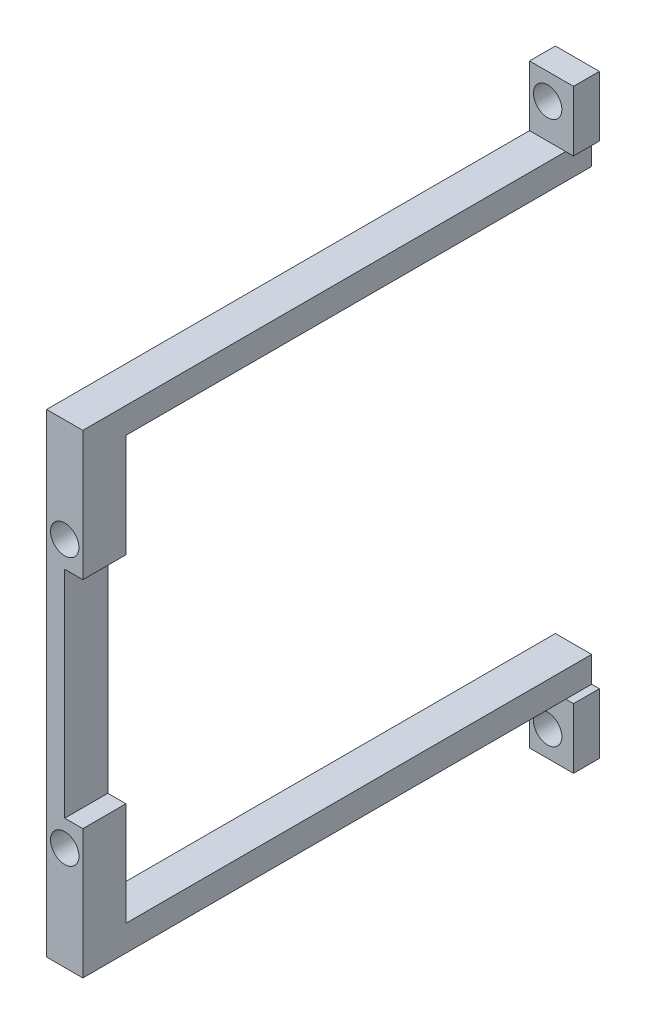
SolidWorks part; units mm, degrees
ref_plane "前视基准面" through (0, 0, 0) normal (0, 0, 1) x (1, 0, 0)
ref_plane "上视基准面" through (0, 0, 0) normal (0, 1, 0) x (1, 0, 0)
ref_plane "右视基准面" through (0, 0, 0) normal (1, 0, 0) x (0, 0, -1)
sketch "草图1" plane through (0, 0, 0) normal (0, 0, 1) x (1, 0, 0)
  line L0 (0, 0) -> (0, -49)
  line L1 (0, -49) -> (4.2, -49)
  line L2 (4.2, -49) -> (4.2, 0)
  line L3 (4.2, 0) -> (0, 0)
extrude "凸台-拉伸1" add sketch "草图1" along normal blind 5
sketch "草图5" plane through (0, 0, 5) normal (0, 0, 1) x (1, 0, 0)
  line L0 (0, -24.5) -> (4.2, -24.5) construction
  line L1 (0, 0) -> (0, -49) construction
  line L2 (4.2, -49) -> (4.2, 0) construction
  line L3 (2.1, -24.5) -> (2.1, -9) construction
  circle A0 centre (2.1, -9) radius 1.65
  circle A1 centre (2.1, -40) radius 1.65
  dimension "D2" = 3.3
  dimension "D1" = 15.5
extrude "切除-拉伸2" cut sketch "草图5" against normal blind 5
sketch "草图6" plane through (0, 0, 5) normal (0, 0, 1) x (1, 0, 0)
  line L0 (0, -49) -> (0, -52)
  line L1 (0, -52) -> (4.2, -52)
  line L2 (4.2, -52) -> (4.2, -49)
  line L3 (4.2, -49) -> (0, -49)
  line L4 (0, -24.5) -> (4.2, -24.5) construction
  line L5 (0, 0) -> (0, -49) construction
  line L6 (4.2, -49) -> (4.2, 0) construction
  line L7 (4.2, 3) -> (4.2, 0)
  line L8 (0, 3) -> (4.2, 3)
  line L9 (0, 0) -> (0, 3)
  line L10 (4.2, 0) -> (0, 0)
  dimension "D1" = 3
  dimension "D2" = 3
extrude "凸台-拉伸2" add sketch "草图6" against normal blind 59
sketch "草图11" plane through (0, 0, -54) normal (0, 0, -1) x (-1, 0, 0)
  line L0 (-2.1, 3) -> (-5.1, 3)
  line L1 (-4.2, 3) -> (0, 3) construction
  line L2 (-2.1, 3) -> (0, 3)
  line L3 (0, 3) -> (0, 10)
  line L4 (0, 10) -> (-5.1, 10)
  line L5 (-5.1, 10) -> (-5.1, 3)
  line L6 (-4.2, -24.5) -> (0, -24.5) construction
  line L7 (-4.2, -49) -> (-4.2, 0) construction
  line L8 (0, 0) -> (0, -49) construction
  line L9 (-2.1, 0) -> (-2.1, 7) construction
  line L10 (0, 0) -> (-4.2, 0) construction
  line L11 (0, -59) -> (-5.1, -59)
  line L12 (0, -52) -> (0, -59)
  line L13 (-2.1, -52) -> (0, -52)
  line L14 (-2.1, -52) -> (-5.1, -52)
  line L15 (-5.1, -59) -> (-5.1, -52)
  circle A0 centre (-2.1, 7) radius 1.65
  circle A1 centre (-2.1, -56) radius 1.65
  dimension "D3" = 2.1
  dimension "D1" = 3
  dimension "D2" = 7
extrude "凸台-拉伸3" add sketch "草图11" against normal blind 3
sketch "草图12" plane through (0, 0, 5) normal (0, 0, 1) x (1, 0, 0)
  line L0 (2.1, -9) -> (2.1, -40) construction
  line L1 (2.1, -9) -> (2.1, -12) construction
  line L2 (2.1, -12) -> (7.6292, -12) construction
  line L3 (2.1, -40) -> (2.1, -37) construction
  line L4 (2.1, -12) -> (2.1, -37)
  line L5 (2.1, -37) -> (9.0561, -37)
  line L6 (9.0561, -37) -> (9.0561, -12)
  line L7 (9.0561, -12) -> (2.1, -12)
  dimension "D1" = 3
  dimension "D2" = 3
extrude "切除-拉伸3" cut sketch "草图12" against normal blind 10
